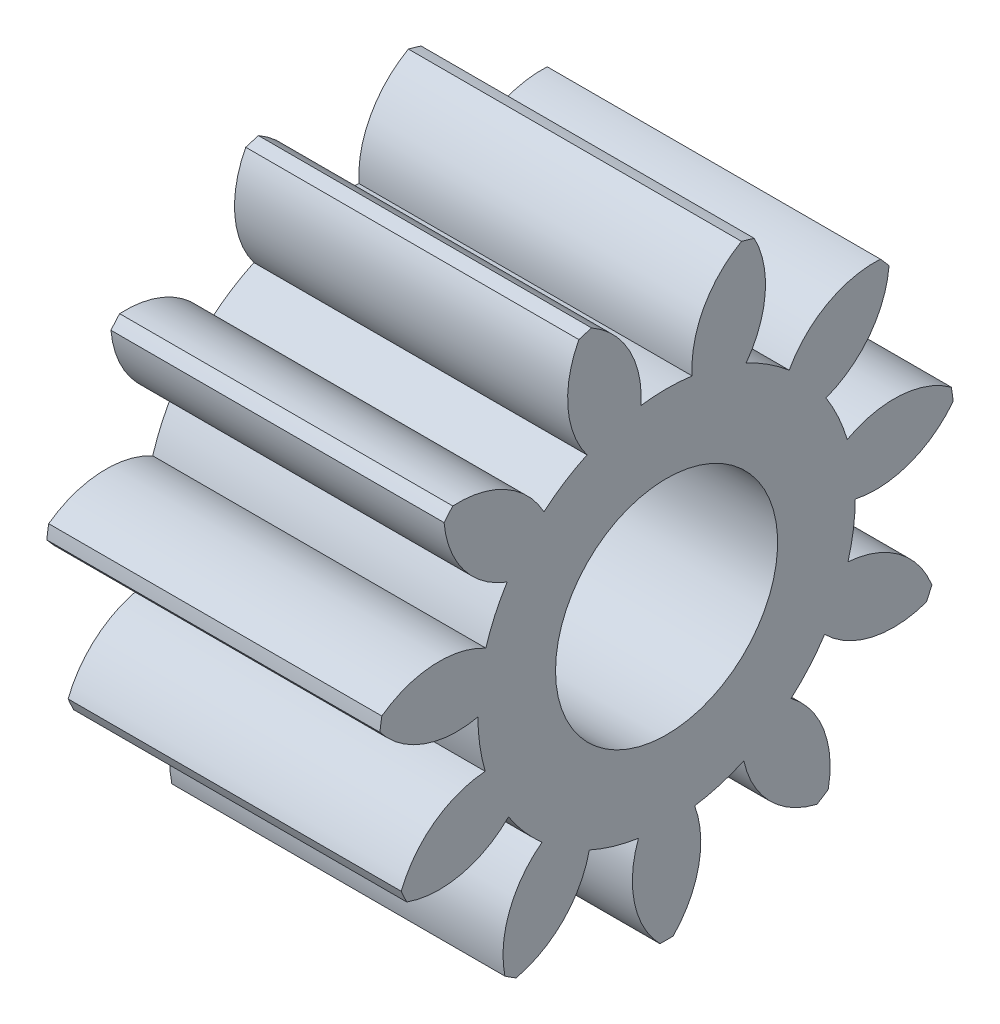
SolidWorks part; units mm, degrees
ref_plane "Plane1" through (0, 0, 0) normal (0, 0, 1) x (1, 0, 0)
ref_plane "Plane2" through (0, 0, 0) normal (0, 1, 0) x (1, 0, 0)
ref_plane "Plane3" through (0, 0, 0) normal (1, 0, 0) x (0, 0, -1)
sketch "HoldingSke" plane through (0, 0, 0) normal (0, 1, 0) x (1, 0, 0)
  line L0 (0, 0) -> (1.636, -0.318)
  line L1 (-15, 0) -> (100, 0) construction
  line L2 (0, 0) -> (-2.1039, 2.3779)
  line L3 (0, 0) -> (-11.863, 4.5341)
  line L4 (0, 0) -> (8.4773, 1.6478)
  line L5 (0, 0) -> (-46.8476, -17.4728)
  line L6 (0, 0) -> (-3.7303, -2.5169)
  line L7 (-2.1039, 2.3779) -> (8.6586, 51.2059)
  line L8 (-76.2, 54.61) -> (-75.7, 54.61)
  line L9 (-71.009, 38.7566) -> (-53.1078, 45.2721)
  line L10 (-76.2, 71.12) -> (104.1128, 71.12)
  line L11 (0, 0) -> (-4.5, 0)
  line L12 (-76.2, 101.6) -> (-76.177, 101.6)
  line L13 (24.9733, 27.94) -> (52.9518, 28.4284)
  line L14 (24.9733, 27.94) -> (24.9743, 27.94)
  line L15 (24.9733, 27.94) -> (100.4006, 29.5858)
  line L16 (-63.627, -0.6) -> (-12.827, -0.6)
  circle A0 centre (0, 0) radius 1.5
  circle A1 centre (0, 0) radius 2.549
  circle A2 centre (0, 0) radius 37.5
  circle A3 centre (0, 0) radius 1.5
  dimension "MHD" = 5.098
  dimension "Hub_dia" = 75
  dimension "Bore" = 3
  dimension "MBD" = 3
  dimension "Num_teeth" = 11
  dimension "Pitch" = 1.6667
  dimension "Overall_len" = 50
  dimension "Show_teeth" = 11
  dimension "Thickness" = 4.5
  dimension "OAL" = 50.0001
  dimension "T_dim" = 0.5
  dimension "Ap" = 20
  dimension "H" = 19.05
  dimension "Pitch_radius" = 180.3128
  dimension "Width" = 4.5
  dimension "Backlash" = 0.023
  dimension "Addendum_fac" = 1
  dimension "Dedendum_fac" = 1.25
  dimension "Clearance_fac" = 0.25
  dimension "Dedendum_add" = 0.001
  dimension "Module" = 0.6
sketch "BasProSke" plane through (0, 0, 0) normal (0, 1, 0) x (1, 0, 0)
  line L0 (-10, 0) -> (60, 0) construction
  line L1 (0, 0) -> (0, 3.9)
  line L2 (0, 0) -> (4.5, 0)
  line L3 (4.5, 0) -> (4.5, 3.9)
  line L4 (4.5, 3.9) -> (0, 3.9)
  dimension "Thickness" = 4.5
  dimension "Diameter" = 7.8
revolve "Base-Revolve" add sketch "BasProSke" angle 360 about L0
sketch "TooCutSke" plane through (0, 0, 0) normal (1, 0, 0) x (0, 0, -1)
  line L1 (0, 0) -> (0, 107) construction
  line L2 (0, 0) -> (-0.5098, 3.2604) construction
  line L3 (0, 0) -> (-1.8436, 6.2788) construction
  line L4 (-0.5098, 3.2604) -> (-0.9218, 3.1394) construction
  arc A0 (0.3459, 2.5254) -> (-0.3459, 2.5254) centre (0, 0) ccw
  arc A1 (1.0446, 3.7839) -> (-1.0446, 3.7839) centre (0, 0) ccw
  circle A2 centre (0, 0) radius 3.3 construction
  circle A3 centre (0, 0) radius 3.101 construction
  arc A4 (-0.3459, 2.5254) -> (-1.0446, 3.7839) centre (-1.6627, 2.6175) ccw
  arc A5 (1.0446, 3.7839) -> (0.3459, 2.5254) centre (1.6627, 2.6175) ccw
  dimension "Root_dia" = 5.098
  dimension "Overcut_dia" = 7.8508
  dimension "Pitch_dia" = 6.6
  dimension "Base_dia" = 6.202
  dimension "Flank_rad" = 1.32
  dimension "Half_ang" = 16.364
  dimension "Half_CT" = 0.4294
extrude "ToothCut" cut sketch "TooCutSke" along normal through all
fillet "Breaks" [suppressed] radius 0.012
fillet "RootFillets" [suppressed] radius 0.151
pattern_circular "TeethCuts" count 11 every 32.727 about axis through (-10, 0, 0) along (1, 0, 0) of "ToothCut", "RootFillets", "Breaks"
sketch "HubNeaOneSke" plane through (0, 0, 0) normal (-1, 0, 0) x (0, 0, 1)
  circle A0 centre (0, 0) radius 2.549
  dimension "Diameter" = 5.098
extrude "HubNearOne" [suppressed] add sketch "HubNeaOneSke" along normal blind 45.5001
sketch "HubNeaBotSke" plane through (0, 0, 0) normal (-1, 0, 0) x (0, 0, 1)
  circle A0 centre (0, 0) radius 2.549
  dimension "Diameter" = 5.098
extrude "HubNearBoth" [suppressed] add sketch "HubNeaBotSke" along normal blind 22.75
ref_plane "FarPln" through (4.5, 0, 0) normal (1, 0, 0) x (0, 0, -1)
sketch "HubFarSke" plane through (4.5, 0, 0) normal (1, 0, 0) x (0, 0, -1)
  circle A0 centre (0, 0) radius 2.549
  dimension "Diameter" = 5.098
extrude "HubFar" [suppressed] add sketch "HubFarSke" along normal blind 22.75
sketch "BorSke" plane through (0, 0, 0) normal (1, 0, 0) x (0, 0, -1)
  circle A0 centre (0, 0) radius 1.5
  dimension "Diameter" = 3
extrude "Bore" cut sketch "BorSke" along normal mid plane 100.0001
sketch "KeySke" plane through (0, 0, 0) normal (1, 0, 0) x (0, 0, -1)
  line L0 (-0.6, 0) -> (-0.6, 2)
  line L1 (-0.6, 2) -> (0.6, 2)
  line L2 (0.6, 2) -> (0.6, 0)
  line L3 (0, 0) -> (0, 34) construction
  line L4 (-0.6, 0) -> (0.6, 0)
  dimension "Offset" = 2
  dimension "Width" = 1.2
extrude "Keyway" [suppressed] cut sketch "KeySke" along normal mid plane 100.0001
pattern_circular "Keyway2" [suppressed] count 2 every 90 about axis through (-10, 0, 0) along (1, 0, 0)
sketch "草图1" plane through (4.5, 0, 0) normal (1, 0, 0) x (0, 0, -1)
  circle A0 centre (0, 0) radius 3.3 construction
  dimension "D1" = 6.6
equation "' \"Module@HoldingSke\" = 6.35"
equation "' \"Num_teeth@HoldingSke\" = 12"
equation "' \"Ap@HoldingSke\" =  20"
equation "' \"Ap@HoldingSke\" = 20"
equation "' \"Width@HoldingSke\" = 0.5 * 25.4"
equation "' \"Hub_dia@HoldingSke\"= 1 * 25.4"
equation "' \"Hub_dia@HoldingSke\" = 1 * 25.4"
equation "' \"Overall_len@HoldingSke\" = 1.0 * 25.4"
equation "' \"Bore@HoldingSke\" = 0.75 * 25.4"
equation "' \"T_dim@HoldingSke\" = 0.1 * 25.4"
equation "' \"Width@KeySke\" = 0.25 * 25.4"
equation "' \"Show_teeth@HoldingSke\" = 13"
equation "' \"Backlash@HoldingSke\" = 0.009 * 25.4"
equation "' \"Addendum_fac@HoldingSke\" = 1.0"
equation "' \"Dedendum_fac@HoldingSke\" = 1.25"
equation "' \"Dedendum_add@HoldingSke\" = 0.00005 * 25.4"
equation "' \"Clearance_fac@HoldingSke\" = 0.25"
equation "\"Pitch@HoldingSke\" = 1 / \"Module@HoldingSke\""
equation "\"Overcut_dia@TooCutSke\" = (\"Num_teeth@HoldingSke\" + 2 * \"Addendum_fac@HoldingSke\") / \"Pitch@HoldingSke\" + 0.002 * 25.4"
equation "\"Pitch_dia@TooCutSke\" = \"Num_teeth@HoldingSke\" / \"Pitch@HoldingSke\""
equation "\"Base_dia@TooCutSke\" = \"Num_teeth@HoldingSke\" / \"Pitch@HoldingSke\" * cos((\"Ap@HoldingSke\"  * 3.14159265 / 180))"
equation "\"Root_dia@TooCutSke\" = (\"Num_teeth@HoldingSke\" + 2) / \"Pitch@HoldingSke\" - 2 * (\"Addendum_fac@HoldingSke\" + \"Dedendum_fac@HoldingSke\") / \"Pitch@HoldingSke\" - \"Dedendum_add@HoldingSke\" * 2"
equation "\"Half_ang@TooCutSke\" = 180 / \"Num_teeth@HoldingSke\""
equation "\"Half_CT@TooCutSke\" = \"Num_teeth@HoldingSke\" / \"Pitch@HoldingSke\" * sin((3.14159265 / 2 / \"Num_teeth@HoldingSke\")) / 2 - 7 * \"Backlash@HoldingSke\" / 4"
equation "\"Flank_rad@TooCutSke\" = \"Num_teeth@HoldingSke\" / \"Pitch@HoldingSke\" / 5"
equation "\"Radius@RootFillets\" = \"Clearance_fac@HoldingSke\" / \"Pitch@HoldingSke\" + \"Dedendum_add@HoldingSke\""
equation "\"Break_rad@Breaks\" = 0.02 / \"Pitch@HoldingSke\""
equation "\"Thickness@HoldingSke\" = \"Width@HoldingSke\""
equation "\"OAL@HoldingSke\" = \"Thickness@HoldingSke\""
equation "\"MHD@HoldingSke\" = (\"Num_teeth@HoldingSke\" + 2) / \"Pitch@HoldingSke\" - 2 * (\"Addendum_fac@HoldingSke\" + \"Dedendum_fac@HoldingSke\")  / \"Pitch@HoldingSke\" - \"Dedendum_add@HoldingSke\" * 2"
equation "\"MBD@HoldingSke\" = (\"Num_teeth@HoldingSke\" + 2) / \"Pitch@HoldingSke\" - 2 * (\"Addendum_fac@HoldingSke\" + \"Dedendum_fac@HoldingSke\")  / \"Pitch@HoldingSke\" - \"Dedendum_add@HoldingSke\" * 2 - 0.002 * 25.4"
equation "\"MHD@HoldingSke\" = ((sgn( \"MHD@HoldingSke\" - \"Hub_dia@HoldingSke\" )-1)*( \"MHD@HoldingSke\" - \"Hub_dia@HoldingSke\" ))/-2+ \"Hub_dia@HoldingSke\""
equation "\"MBD@HoldingSke\" = ((sgn( \"MBD@HoldingSke\" - \"Bore@HoldingSke\" )-1)*( \"MBD@HoldingSke\" - \"Bore@HoldingSke\" ))/-2+ \"Bore@HoldingSke\""
equation "\"OAL@HoldingSke\" = ((sgn( \"OAL@HoldingSke\" - \"Overall_len@HoldingSke\" )+1)*( \"OAL@HoldingSke\" - \"Overall_len@HoldingSke\" ))/2 + \"Overall_len@HoldingSke\" + 0.000002 * 25.4"
equation "\"Num_teeth@TeethCuts\" = int( \"Show_teeth@HoldingSke\" ) + 1"
equation "\"Num_teeth@TeethCuts\" = ((sgn( \"Num_teeth@TeethCuts\" - \"Num_teeth@HoldingSke\" )-1)*( \"Num_teeth@TeethCuts\" - \"Num_teeth@HoldingSke\" ))/-2+ \"Num_teeth@HoldingSke\""
equation "\"Num_teeth@TeethCuts\" = ((sgn( \"Num_teeth@TeethCuts\" - 2.0)+1)*( \"Num_teeth@TeethCuts\" - 2.0))/2 +2.0"
equation "\"Angle@TeethCuts\" = 360.0 / \"Num_teeth@HoldingSke\""
equation "\"Diameter@BasProSke\" = (\"Num_teeth@HoldingSke\" + 2 * \"Addendum_fac@HoldingSke\") / \"Pitch@HoldingSke\""
equation "\"Thickness@BasProSke\"  = \"Thickness@HoldingSke\""
equation "' \"Fillet_rad@BasProSke\" =  \"Thickness@HoldingSke\" * 0.05"
equation "' \"Fillet_rad@BasProSke\" = \"Thickness@HoldingSke\" * 0.05"
equation "\"MHD@HoldingSke\" = ((sgn( \"MHD@HoldingSke\" - \"Root_dia@TooCutSke\" )-1)*( \"MHD@HoldingSke\" - \"Root_dia@TooCutSke\" ))/-2+ \"Root_dia@TooCutSke\""
equation "\"Diameter@HubNeaOneSke\" = \"MHD@HoldingSke\""
equation "\"Length@HubNearOne\" = \"OAL@HoldingSke\" - \"Thickness@BasProSke\""
equation "\"Diameter@HubNeaBotSke\" = \"MHD@HoldingSke\""
equation "\"Length@HubNearBoth\" = ( \"OAL@HoldingSke\" - \"Thickness@BasProSke\" ) / 2.0"
equation "\"Thickness@FarPln\" = \"Thickness@BasProSke\""
equation "\"Diameter@HubFarSke\" = \"MHD@HoldingSke\""
equation "\"Length@HubFar\" = ( \"OAL@HoldingSke\" - \"Thickness@BasProSke\" ) / 2.0"
equation "\"Diameter@BorSke\" = \"MBD@HoldingSke\""
equation "\"D1@Bore\" = \"OAL@HoldingSke\" * 2.0"
equation "\"D1@Keyway\" = \"OAL@HoldingSke\" * 2.0"
equation "\"Offset@KeySke\" = \"T_dim@HoldingSke\" + \"MBD@HoldingSke\" / 2.0"
